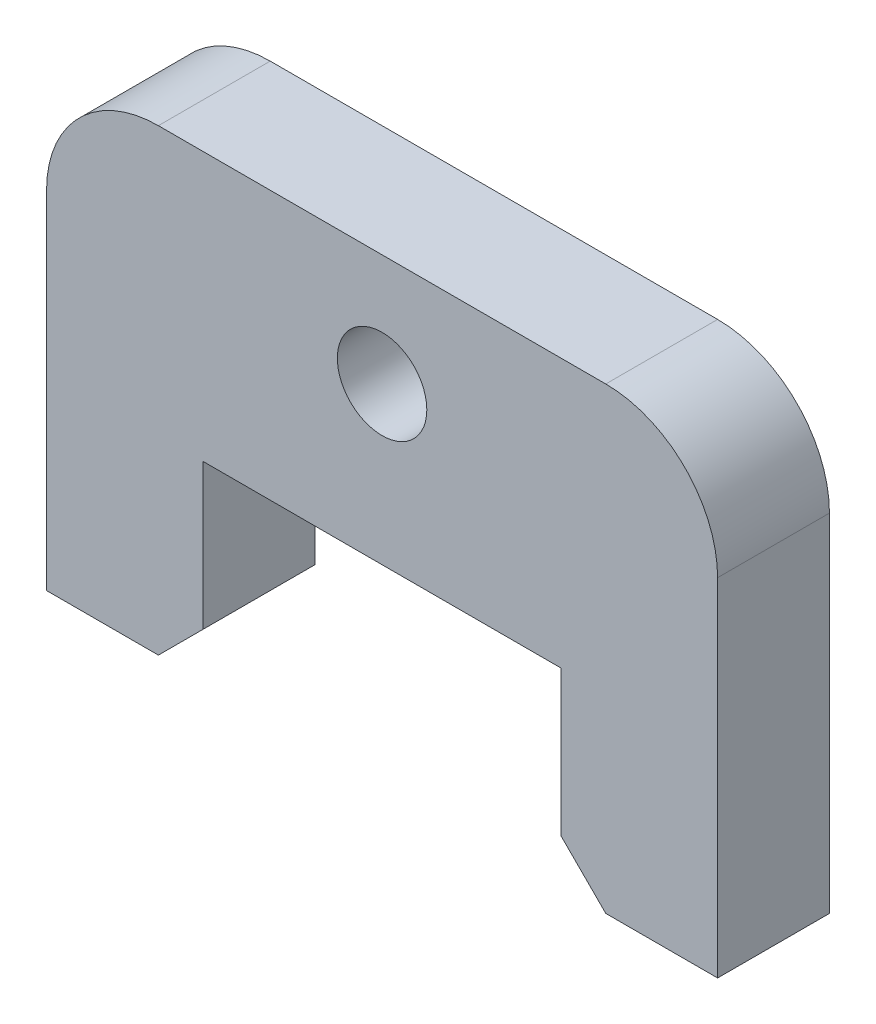
SolidWorks part; units mm, degrees
ref_plane "Front Plane" through (0, 0, 0) normal (0, 0, 1) x (1, 0, 0)
ref_plane "Top Plane" through (0, 0, 0) normal (0, 1, 0) x (1, 0, 0)
ref_plane "Right Plane" through (0, 0, 0) normal (1, 0, 0) x (0, 0, -1)
sketch "Sketch1" plane through (0, 0, 0) normal (0, 0, 1) x (1, 0, 0)
  line L0 (0, 0) -> (0, 31)
  line L1 (0, 0) -> (10, 0)
  line L2 (10, 0) -> (14.0022, 4.0022)
  line L3 (14.0022, 4.0022) -> (14.0022, 17)
  line L4 (14.0022, 17) -> (46.0022, 17)
  line L5 (46.0022, 17) -> (46.0022, 4.0022)
  line L6 (46.0022, 4.0022) -> (50.0044, 0)
  line L7 (50.0044, 0) -> (60.0044, 0)
  line L8 (60.0044, 0) -> (60.0044, 31)
  line L9 (50.0044, 41) -> (10, 41)
  circle A0 centre (30.0022, 31) radius 4
  arc A1 (0, 31) -> (10, 41) centre (10, 31) cw
  arc A2 (60.0044, 31) -> (50.0044, 41) centre (50.0044, 31) ccw
  point P13 (0, 0)
  point P14 (30.0022, 41)
  point P15 (0, 0)
  point P18 (0, 41)
  point P21 (0, 0)
  dimension "D7" = 8
  dimension "D8" = 10
  dimension "D1" = 10
  dimension "D2" = 41
  dimension "D3" = 17
  dimension "D4" = 32
  dimension "D5" = 5.66
  dimension "D6" = 135
extrude "Boss-Extrude1" add sketch "Sketch1" along normal blind 10
sketch "Sketch2" plane through (0, 0, 0) normal (0, -1, 0) x (1, 0, 0)
  line L0 (50.0044, 0) -> (60.0044, 0) construction
  line L1 (60.0044, 10) -> (60.0044, 0) construction
  circle A0 centre (55.0044, 5) radius 2.5
  point P2 (0, 0)
  point P5 (55.0044, 0)
  point P8 (60.0044, 5)
  dimension "D1" = 5
extrude "Cut-Extrude1" cut sketch "Sketch2" against normal blind 8
sketch "Sketch3" plane through (0, 0, 0) normal (0, -1, 0) x (1, 0, 0)
  line L0 (0, 10) -> (0, 0) construction
  circle A0 centre (5, 5) radius 2.5
  point P2 (0, 0)
  point P5 (0, 5)
  dimension "D1" = 5
extrude "Cut-Extrude2" cut sketch "Sketch3" against normal blind 8
